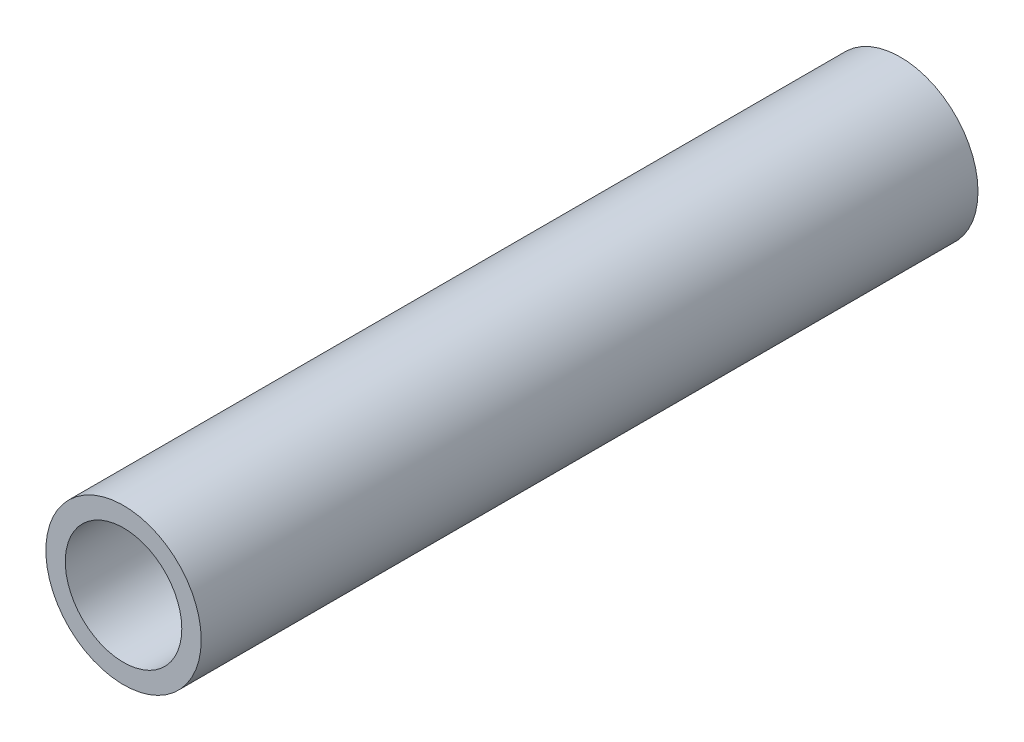
SolidWorks part; units mm, degrees
material "Thornel Mat VMA"
ref_plane "前视基准面" through (0, 0, 0) normal (0, 0, 1) x (1, 0, 0)
ref_plane "上视基准面" through (0, 0, 0) normal (0, 1, 0) x (1, 0, 0)
ref_plane "右视基准面" through (0, 0, 0) normal (1, 0, 0) x (0, 0, -1)
sketch "草图1" plane through (0, 0, 0) normal (0, 0, 1) x (1, 0, 0)
  circle A0 centre (0, 0) radius 4
  circle A1 centre (0, 0) radius 3
  dimension "D1" = 8
  dimension "D2" = 6
extrude "凸台-拉伸1" add sketch "草图1" along normal blind 40
